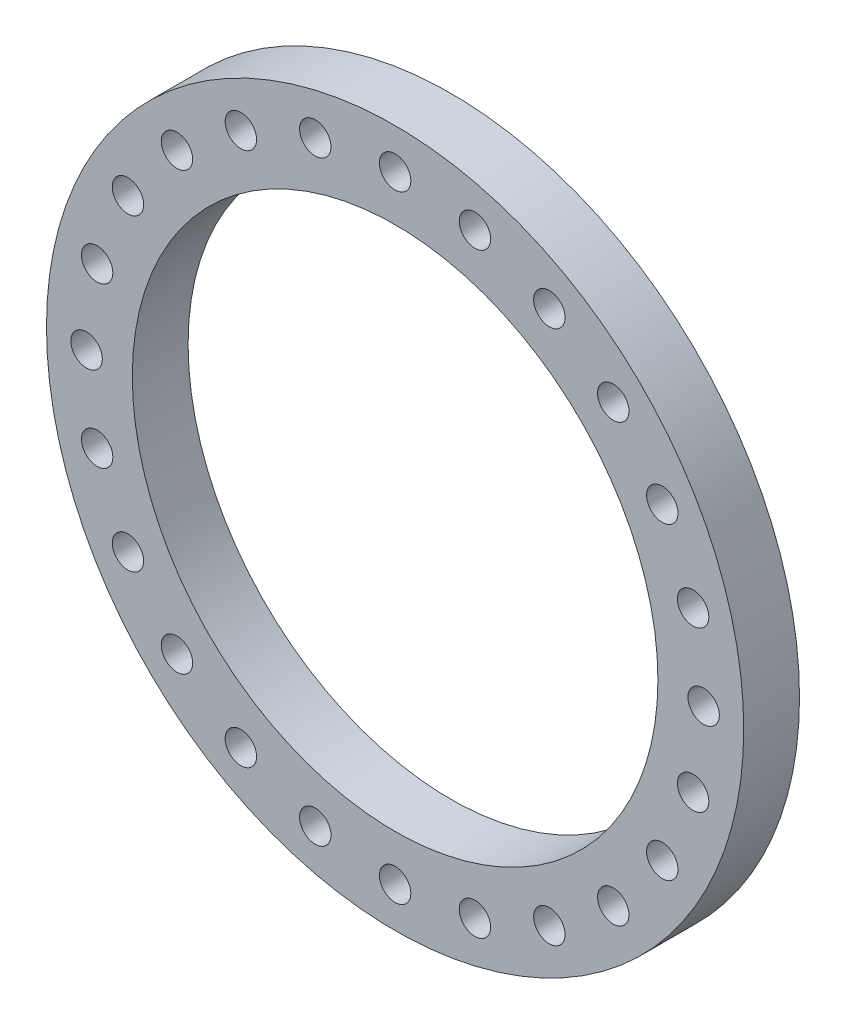
SolidWorks part; units mm, degrees
ref_plane "Front Plane" through (0, 0, 0) normal (0, 0, 1) x (1, 0, 0)
ref_plane "Top Plane" through (0, 0, 0) normal (0, 1, 0) x (1, 0, 0)
ref_plane "Right Plane" through (0, 0, 0) normal (1, 0, 0) x (0, 0, -1)
sketch "Sketch1" plane through (0, 0, 0) normal (0, 0, 1) x (1, 0, 0)
  circle A0 centre (0, 0) radius 387.5
  dimension "D1" = 775
extrude "Boss-Extrude1" add sketch "Sketch1" along normal blind 62
sketch "Sketch3" plane through (0, 0, 62) normal (0, 0, 1) x (1, 0, 0)
  circle A0 centre (0, 0) radius 342.9 construction
  circle A1 centre (0, 342.9) radius 17.4625
  dimension "D1" = 685.8
  dimension "D2" = 34.925
extrude "Cut-Extrude1" cut sketch "Sketch3" against normal through all both and the other way through all contours A1
sketch "Sketch2" plane through (0, 0, 62) normal (0, 0, 1) x (1, 0, 0)
  circle A0 centre (0, 0) radius 292.1
  dimension "D1" = 584.2
extrude "Boss-Extrude2" add sketch "Sketch2" along normal blind 1.5
pattern_circular "CirPattern1" count 24 over 360 about axis through (0, 0, 0) along (0, 0, 1) of "Cut-Extrude1"
sketch "Sketch8" plane through (0, 0, 63.5) normal (0, 0, 1) x (1, 0, 0)
  circle A1 centre (0, 0) radius 292.1
  circle A2 centre (0, 0) radius 292.1
  dimension "D1" = 0
extrude "Cut-Extrude4" cut sketch "Sketch8" against normal through all both and the other way through all
sketch "Sketch4" [suppressed] plane through (0, 0, 0) normal (0, 0, -1) x (-1, 0, 0)
  line L0 (0, -292.1) -> (0, 292.1)
  circle A0 centre (0, 0) radius 292.1 construction
  point P5 (0, 0)
split "Split1" [suppressed] bodies to split 104
sketch "Sketch6" [suppressed] plane through (0, 0, 63.5) normal (0, 0, 1) x (1, 0, 0)
  line L1 (0, -292.1) -> (0, 292.1) construction
  circle A0 centre (-20, 0) radius 11.1
  dimension "D1" = 22.2
  dimension "D2" = 20
extrude "Cut-Extrude2" [suppressed] cut sketch "Sketch6" against normal through all both and the other way through all
other "Fill Pattern1" [suppressed] parameters "D5"=0, "D6"=0, "D1"=27, "D2"=32, "D3"=15, "D9"=153, "D7"=18, "D8"=17
sketch "Sketch7" [suppressed] plane through (0, 0, 63.5) normal (0, 0, 1) x (1, 0, 0)
  line L0 (0, -292.1) -> (0, 292.1) construction
  circle A0 centre (20, 0) radius 11.1
  dimension "D1" = 22.2
  dimension "D2" = 20
extrude "Cut-Extrude3" [suppressed] cut sketch "Sketch7" against normal through all
other "Fill Pattern2" [suppressed] parameters "D5"=0, "D6"=0, "D1"=27, "D2"=32, "D3"=15, "D9"=153, "D7"=18, "D8"=17
